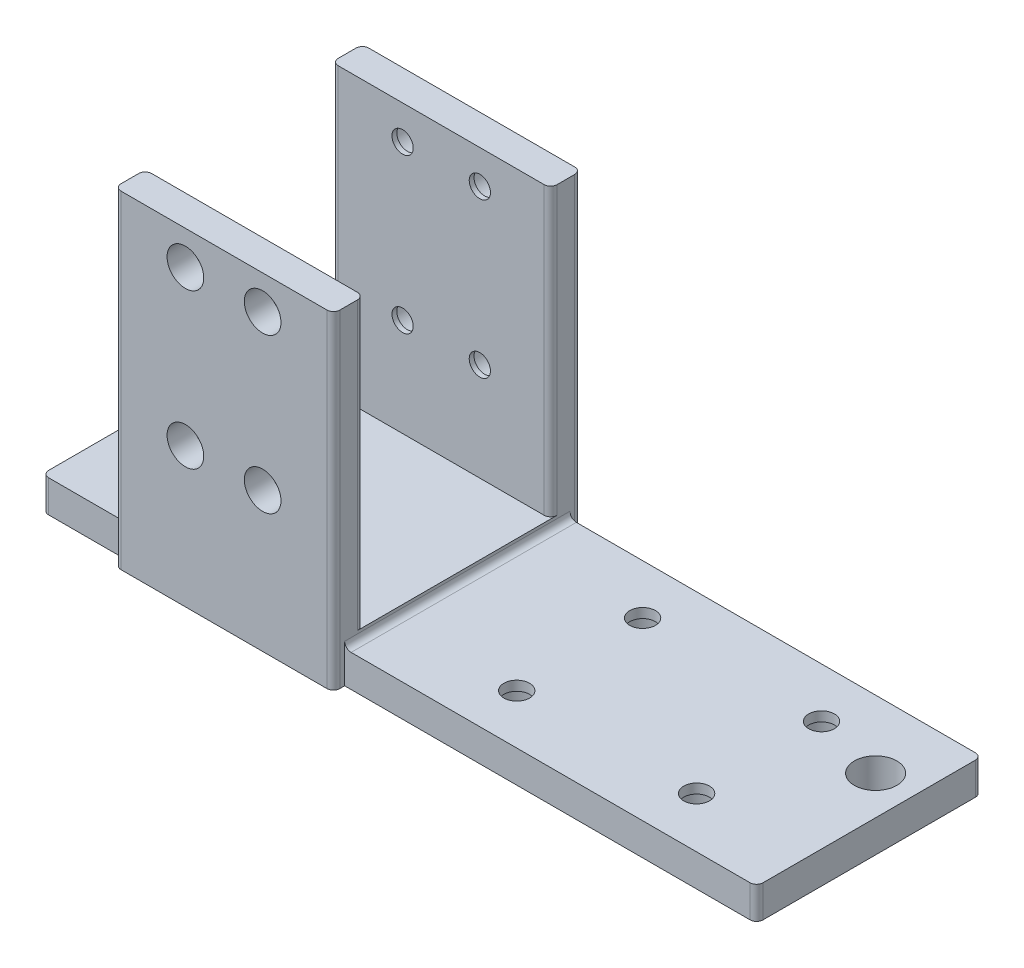
SolidWorks part; units mm, degrees
material "ABS"
ref_plane "Front Plane" through (0, 0, 0) normal (0, 0, 1) x (1, 0, 0)
ref_plane "Top Plane" through (0, 0, 0) normal (0, 1, 0) x (1, 0, 0)
ref_plane "Right Plane" through (0, 0, 0) normal (1, 0, 0) x (0, 0, -1)
sketch "Sketch1" plane through (0, 0, 0) normal (0, 1, 0) x (1, 0, 0)
  line L1 (-52.5, -17.5) -> (52.5, -17.5)
  line L2 (-52.5, -17.5) -> (-52.5, 17.5)
  line L3 (-52.5, 17.5) -> (52.5, 17.5)
  line L4 (52.5, -17.5) -> (52.5, 17.5)
  line L5 (-52.5, -17.5) -> (52.5, 17.5) construction
  line L6 (-52.5, 17.5) -> (52.5, -17.5) construction
  point P0 (0, 0)
  dimension "D1" = 35
  dimension "D2" = 105
extrude "Boss-Extrude1" add sketch "Sketch1" along normal blind 5
sketch "Sketch4" plane through (0, 5, 0) normal (0, 1, 0) x (1, 0, 0)
  line L0 (52.5, 17.5) -> (-52.5, 17.5) construction
  line L1 (-7.9, 17.5) -> (-41.1, 17.5)
  line L2 (-7.9, 17.5) -> (-7.9, -17.5)
  line L3 (-7.9, -17.5) -> (-41.1, -17.5)
  line L4 (-41.1, 17.5) -> (-41.1, -17.5)
  line L5 (-52.5, -17.5) -> (52.5, -17.5) construction
  line L6 (-7.9, -12.25) -> (-7.9, 12.25) construction
  line L7 (-41.1, 12.25) -> (-41.1, 3.5) construction
extrude "Boss-Extrude2" add sketch "Sketch4" along normal up to surface (1.45 mm away)
ref_plane "Plane1" through (-24.5, 0, 0) normal (-1, 0, 0) x (0, 0, 1)
sketch "Sketch5" plane through (-24.5, 0, 0) normal (-1, 0, 0) x (0, 0, 1)
  line L0 (-17.5, 0) -> (-19.25, 0)
  line L1 (-19.25, 0) -> (-19.25, 50.95)
  line L2 (-19.25, 50.95) -> (-14.25, 50.95)
  line L3 (-14.25, 50.95) -> (-14.25, 6.45)
  line L4 (-14.25, 6.45) -> (-17.5, 6.45)
  line L5 (-17.5, 6.45) -> (-17.5, 0)
  line L6 (-14.25, 50.95) -> (-14.25, 38.7) construction
  dimension "D1" = 5
extrude "Boss-Extrude3" add sketch "Sketch5" along normal up to surface (17 mm away) and the other way up to surface (17 mm away)
hole_wizard "CBORE for M2.5 SHCS1" positions "Sketch8" profile "Sketch9" counterbore size "M2.5" standard "ANSI Metric"
sketch "Sketch8" plane through (0, 0, -19.25) normal (0, 0, -1) x (-1, 0, 0)
  point P0 (30.5, 45.7)
  point P3 (18.5, 45.7)
  point P6 (30.5, 21.7)
  point P9 (18.5, 21.7)
sketch "Sketch9" plane through (-30.5, 45.7, -19.25) normal (1, 0, 0) x (0, 1, 0)
  line L0 (0, 0) -> (0, 34.4904)
  line L1 (0, 34.4904) -> (1.65, 33.499)
  line L2 (1.65, 33.499) -> (1.65, 4)
  line L3 (1.65, 4) -> (2.85, 4)
  line L4 (2.85, 4) -> (2.85, 0)
  line L5 (2.85, 0) -> (0, 0)
  line L10 (0, 34.4904) -> (-1.65, 33.499) construction
  line L11 (0, -6.35) -> (0, 107.95) construction
  dimension "Hole Dia." = 3.3
  dimension "Hole Depth" = 33.499
  dimension "C'Bore Dia." = 5.7
  dimension "C'Bore Depth" = 4
  dimension "Drill Angle" = 118
ref_plane "Plane2" through (0, 0, 0) normal (0, 0, -1) x (-1, 0, 0)
mirror "Mirror1" about plane through (0, 0, 0) normal (0, 0, -1) of "CBORE for M2.5 SHCS1", "Boss-Extrude3"
sketch "Sketch11" plane through (-7.9, 0, 0) normal (1, 0, 0) x (0, 0, -1)
  line L6 (17.5, 5) -> (17.5, 6.45)
  line L7 (17.5, 6.45) -> (14.25, 6.45)
  line L8 (14.25, 6.45) -> (-14.25, 6.45)
  line L9 (-14.25, 6.45) -> (-17.5, 6.45)
  line L10 (-17.5, 6.45) -> (-17.5, 5)
  line L11 (-17.5, 5) -> (17.5, 5)
  line L12 (17.5, 5) -> (17.5, 6.45)
  line L13 (17.5, 6.45) -> (14.25, 6.45)
  line L14 (14.25, 6.45) -> (-14.25, 6.45)
  line L15 (-14.25, 6.45) -> (-17.5, 6.45)
  line L16 (-17.5, 6.45) -> (-17.5, 5)
  line L17 (-17.5, 5) -> (17.5, 5)
  dimension "D1" = 0
extrude "Boss-Extrude5" add sketch "Sketch11" along normal up to surface (0.4 mm away) up to face at (-7.5, 17.1143, 17.0714)
sketch "Sketch12" plane through (-41.1, 0, 0) normal (-1, 0, 0) x (0, 0, 1)
  line L6 (17.5, 5) -> (17.5, 6.45)
  line L7 (17.5, 6.45) -> (14.25, 6.45)
  line L8 (14.25, 6.45) -> (-14.25, 6.45)
  line L9 (-14.25, 6.45) -> (-17.5, 6.45)
  line L10 (-17.5, 6.45) -> (-17.5, 5)
  line L11 (-17.5, 5) -> (17.5, 5)
  line L12 (17.5, 5) -> (17.5, 6.45)
  line L13 (17.5, 6.45) -> (14.25, 6.45)
  line L14 (14.25, 6.45) -> (-14.25, 6.45)
  line L15 (-14.25, 6.45) -> (-17.5, 6.45)
  line L16 (-17.5, 6.45) -> (-17.5, 5)
  line L17 (-17.5, 5) -> (17.5, 5)
  dimension "D1" = 0
extrude "Boss-Extrude6" add sketch "Sketch12" along normal up to surface (0.4 mm away) up to face at (-41.5, 17.1143, -17.0714)
hole_wizard "CBORE for #6 Socket Head Cap Screw1" positions "Sketch13" profile "Sketch14" counterbore size "#6" standard "ANSI Inch" end condition up to next
sketch "Sketch13" plane through (0, 0, 0) normal (0, -1, 0) x (-1, 0, 0)
  point P0 (-39.325, 9.779)
  point P2 (-11.514, 9.779)
  point P4 (-39.325, -9.6397)
  point P6 (-11.514, -9.779)
sketch "Sketch14" plane through (39.325, 0, -9.779) normal (1, 0, 0) x (0, 0, -1)
  line L0 (0, 0) -> (0, 5)
  line L1 (0, 5) -> (1.9987, 5)
  line L3 (1.9987, 5) -> (1.9987, 3.5052)
  line L4 (1.9987, 3.5052) -> (3.6725, 3.5052)
  line L5 (3.6725, 3.5052) -> (3.6725, 0)
  line L7 (3.6725, 0) -> (0, 0)
  line L11 (0, -6.35) -> (0, 107.95) construction
  dimension "Thru Hole Dia." = 3.9973
  dimension "Thru Hole Depth" = 5
  dimension "C'Bore Dia." = 7.345
  dimension "C'Bore Depth" = 3.5052
sketch "Sketch15" plane through (0, 0, 0) normal (0, 0, -1) x (-1, 0, 0)
  line L4 (41.5, 50.95) -> (7.5, 50.95)
  line L5 (41.5, 6.45) -> (41.5, 50.95)
  line L6 (7.5, 6.45) -> (41.5, 6.45)
  line L7 (7.5, 50.95) -> (7.5, 6.45)
  line L8 (41.5, 50.95) -> (7.5, 50.95)
  line L9 (41.5, 6.45) -> (41.5, 50.95)
  line L10 (7.5, 6.45) -> (41.5, 6.45)
  line L11 (7.5, 50.95) -> (7.5, 6.45)
  dimension "D1" = 0
extrude "Cut-Extrude1" cut sketch "Sketch15" against normal mid plane 29
sketch "Sketch16" plane through (-52.5, 0, 0) normal (-1, 0, 0) x (0, 0, 1)
  line L4 (-17.5, 0) -> (17.5, 0)
  line L5 (17.5, 0) -> (17.5, 5)
  line L6 (17.5, 5) -> (-17.5, 5)
  line L7 (-17.5, 5) -> (-17.5, 0)
  line L8 (-17.5, 0) -> (17.5, 0)
  line L9 (17.5, 0) -> (17.5, 5)
  line L10 (17.5, 5) -> (-17.5, 5)
  line L11 (-17.5, 5) -> (-17.5, 0)
  dimension "D1" = 0
extrude "Boss-Extrude7" add sketch "Sketch16" along normal blind 2
sketch "Sketch17" plane through (52.5, 0, 0) normal (1, 0, 0) x (0, 0, -1)
  line L4 (-17.5, 0) -> (17.5, 0)
  line L5 (17.5, 0) -> (17.5, 5)
  line L6 (17.5, 5) -> (-17.5, 5)
  line L7 (-17.5, 5) -> (-17.5, 0)
  line L8 (-17.5, 0) -> (17.5, 0)
  line L9 (17.5, 0) -> (17.5, 5)
  line L10 (17.5, 5) -> (-17.5, 5)
  line L11 (-17.5, 5) -> (-17.5, 0)
  dimension "D1" = 0
extrude "Boss-Extrude8" add sketch "Sketch17" along normal blind 4
hole_wizard "M6 Clearance Hole1" positions "Sketch2" profile "Sketch3" hole size "M6" standard "ANSI Metric" end condition through all
sketch "Sketch2" plane through (0, 5, 0) normal (0, 1, 0) x (1, 0, 0)
  line L4 (-54.5, -17.5) -> (-54.5, 17.5) construction
  line L5 (-41.5, 17.5) -> (-54.5, 17.5) construction
  line L6 (56.5, 17.5) -> (56.5, -17.5) construction
  point P0 (-48.5, 7)
  point P2 (50.5, 7)
  dimension "D1" = 6
  dimension "D2" = 6
  dimension "D3" = 10.5
sketch "Sketch3" plane through (-48.5, 5, -7) normal (1, 0, 0) x (0, 0, 1)
  line L0 (0, 0) -> (0, 5)
  line L1 (0, 5) -> (3.3, 5)
  line L2 (3.3, 5) -> (3.3, 0)
  line L5 (3.3, 0) -> (0, 0)
  line L11 (0, -6.35) -> (0, 107.95) construction
  dimension "Thru Hole Dia." = 6.6
  dimension "Thru Hole Depth" = 5
fillet "Fillet1" radius 1 14 edges at (56.5, 2.5, -17.5) (56.5, 2.5, 17.5) (-7.5, 5, 0) (-41.5, 25.475, -19.25) (-7.5, 25.475, -19.25) (-7.5, 28.7, -14.5) (-41.5, 28.7, -14.5) (-7.5, 28.7, 14.5) (-41.5, 28.7, 14.5) (-41.5, 25.475, 19.25) (-7.5, 25.475, 19.25) (-41.5, 5, 0) (-54.5, 2.5, -17.5) (-54.5, 2.5, 17.5)
